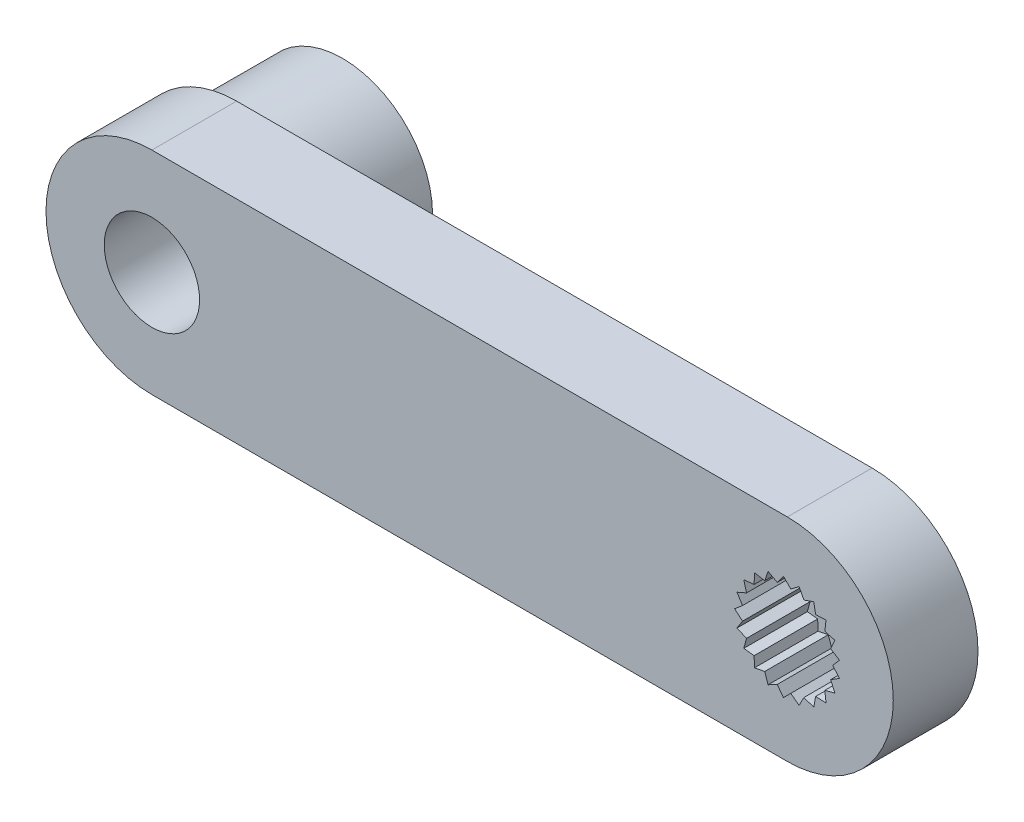
SolidWorks part; units mm, degrees
material "PET"
ref_plane "Front Plane" through (0, 0, 0) normal (0, 0, 1) x (1, 0, 0)
ref_plane "Top Plane" through (0, 0, 0) normal (0, 1, 0) x (1, 0, 0)
ref_plane "Right Plane" through (0, 0, 0) normal (1, 0, 0) x (0, 0, -1)
sketch "Sketch1" plane through (0, 0, 0) normal (0, 0, 1) x (1, 0, 0)
  line L0 (0, 0) -> (30, 0) construction
  line L1 (0, 5) -> (30, 5)
  line L2 (0, -5) -> (30, -5)
  arc A0 (0, 5) -> (0, -5) centre (0, 0) ccw
  arc A1 (30, -5) -> (30, 5) centre (30, 0) ccw
  circle A2 centre (0, 0) radius 2.25
  circle A4 centre (30, 0) radius 1
  point P3 (15, 0)
  dimension "D1" = 5
  dimension "D3" = 4.5
  dimension "D4" = 2
  dimension "D2" = 30
extrude "Boss-Extrude1" add sketch "Sketch1" along normal mid plane 4
sketch "Sketch2" plane through (0, 0, 2) normal (0, 0, 1) x (1, 0, 0)
  circle A0 centre (30, 0) radius 2.49
  circle A1 centre (30, 0) radius 1 construction
  dimension "D1" = 4.98
extrude "Cut-Extrude1" cut sketch "Sketch2" against normal blind 3
sketch "Sketch3" plane through (0, 0, -2) normal (0, 0, -1) x (-1, 0, 0)
  circle A2 centre (-30, 0) radius 3
  circle A4 centre (-30, 0) radius 1 construction
  circle A5 centre (-30, 0) radius 1
  dimension "D1" = 6
extrude "Boss-Extrude2" add sketch "Sketch3" along normal blind 1
sketch "Sketch4" plane through (0, 0, -2) normal (0, 0, -1) x (-1, 0, 0)
  circle A0 centre (0, 0) radius 2.25 construction
  circle A1 centre (0, 0) radius 2.25
  circle A2 centre (0, 0) radius 4.25
  dimension "D1" = 2
extrude "Boss-Extrude3" add sketch "Sketch4" along normal blind 5
sketch "Sketch5" plane through (0, 0, 2) normal (0, 0, 1) x (1, 0, 0)
  line L0 (30, 0) -> (32.49, 0) construction
  line L3 (30, 0) -> (32.4622, 0.3711) construction
  line L4 (32.4622, 0.3711) -> (32.14, 0)
  line L5 (32.14, 0) -> (32.4622, -0.3711)
  circle A0 centre (30, 0) radius 2.49 construction
  arc A1 (32.4622, -0.3711) -> (32.4622, 0.3711) centre (30, 0) ccw
  dimension "D1" = 8.571
  dimension "D2" = 0.35
extrude "Boss-Extrude4" add sketch "Sketch5" against normal blind 3.2
pattern_circular "CirPattern2" count 21 over 360 about axis through (30, 0, 0) along (0, 0, 1) of "Boss-Extrude4"
